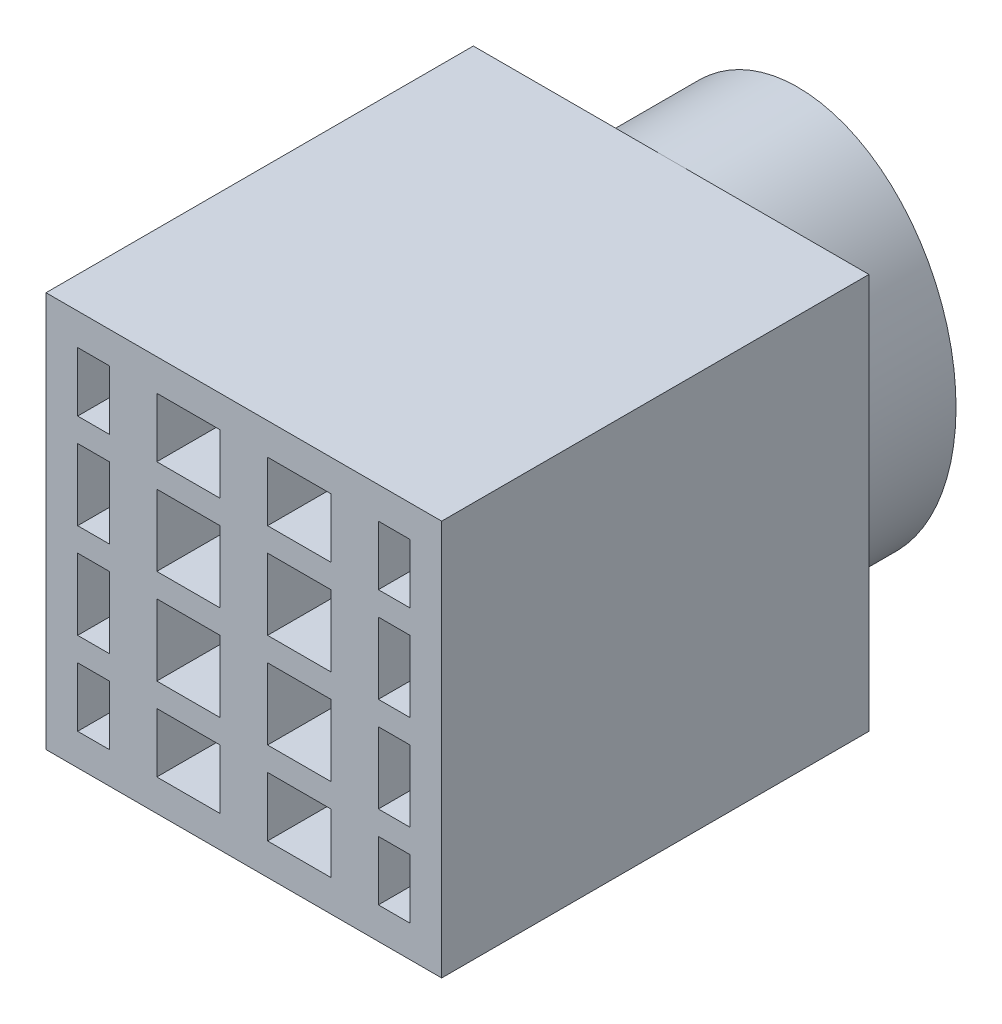
SolidWorks part; units mm, degrees
ref_plane "前视基准面" through (0, 0, 0) normal (0, 0, 1) x (1, 0, 0)
ref_plane "上视基准面" through (0, 0, 0) normal (0, 1, 0) x (1, 0, 0)
ref_plane "右视基准面" through (0, 0, 0) normal (1, 0, 0) x (0, 0, -1)
sketch "草图8" plane through (0, 0, 0) normal (0, 0, 1) x (1, 0, 0)
  line L0 (0, 7.8741) -> (0, -9.2542) construction
  line L1 (-12.5, -12.5) -> (12.5, -12.5)
  line L2 (-12.5, -12.5) -> (-12.5, 12.5)
  line L3 (-12.5, 12.5) -> (12.5, 12.5)
  line L4 (12.5, -12.5) -> (12.5, 12.5)
  line L5 (-12.5, -12.5) -> (12.5, 12.5) construction
  line L6 (-12.5, 12.5) -> (12.5, -12.5) construction
  line L7 (-16.0619, 0) -> (15.5648, 0) construction
  line L8 (-3.5, 7.8741) -> (-3.5, -9.2542) construction
  line L9 (-9.5, 7.8741) -> (-9.5, -9.2542) construction
  line L10 (5.5, 10.5) -> (1.5, 10.5)
  line L15 (-5.5, -10.5) -> (-1.5, -10.5)
  line L20 (-5.5, -10.5) -> (-5.5, 10.5)
  line L21 (-5.5, 10.5) -> (-1.5, 10.5)
  line L26 (-1.5, -10.5) -> (-1.5, 10.5)
  line L27 (-5.5, -10.5) -> (-1.5, 10.5) construction
  line L28 (-5.5, 10.5) -> (-1.5, -10.5) construction
  line L29 (-10.5, -10.5) -> (-8.5, -10.5)
  line L30 (-10.5, -10.5) -> (-10.5, 10.5)
  line L31 (-10.5, 10.5) -> (-8.5, 10.5)
  line L32 (-8.5, -10.5) -> (-8.5, 10.5)
  line L33 (-10.5, -10.5) -> (-8.5, 10.5) construction
  line L34 (-10.5, 10.5) -> (-8.5, -10.5) construction
  line L35 (1.5, -10.5) -> (1.5, 10.5)
  line L36 (5.5, -10.5) -> (1.5, -10.5)
  line L37 (5.5, -10.5) -> (5.5, 10.5)
  line L38 (10.5, 10.5) -> (8.5, 10.5)
  line L39 (8.5, -10.5) -> (8.5, 10.5)
  line L40 (10.5, -10.5) -> (8.5, -10.5)
  line L41 (10.5, -10.5) -> (10.5, 10.5)
  point P0 (0, 0)
  point P14 (-7, 0)
  point P15 (-3.5, 0)
  point P17 (-3, 0)
  point P21 (-9.5, 0)
  point P22 (-9, 0)
  dimension "D1" = 3.5
  dimension "D2" = 6
extrude "凸台-拉伸7" add sketch "草图8" along normal blind 25
sketch "草图9" plane through (0, 0, 0) normal (0, 0, -1) x (-1, 0, 0)
  line L1 (-12.5, -12.5) -> (12.5, -12.5)
  line L2 (-12.5, -12.5) -> (-12.5, 12.5)
  line L3 (-12.5, 12.5) -> (12.5, 12.5)
  line L4 (12.5, -12.5) -> (12.5, 12.5)
  line L5 (-12.5, -12.5) -> (12.5, 12.5) construction
  line L6 (-12.5, 12.5) -> (12.5, -12.5) construction
  point P0 (0, 0)
extrude "凸台-拉伸8" add sketch "草图9" along normal blind 2
sketch "草图14" plane through (0, 0, 25) normal (0, 0, 1) x (1, 0, 0)
  line L0 (-16.6961, 0) -> (20.7273, 0) construction
  line L1 (-12.5, 12.5) -> (-12.5, -12.5) construction
  line L2 (12.5, -0.75) -> (-12.5, -0.75)
  line L3 (12.5, -0.75) -> (12.5, 0.75)
  line L4 (12.5, 0.75) -> (-12.5, 0.75)
  line L5 (-12.5, -0.75) -> (-12.5, 0.75)
  line L6 (12.5, -0.75) -> (-12.5, 0.75) construction
  line L7 (12.5, 0.75) -> (-12.5, -0.75) construction
  line L12 (12.5, 5.25) -> (-12.5, 5.25)
  line L13 (12.5, 5.25) -> (12.5, 6.75)
  line L14 (12.5, 6.75) -> (-12.5, 6.75)
  line L15 (-12.5, 5.25) -> (-12.5, 6.75)
  line L16 (12.5, 5.25) -> (-12.5, 6.75) construction
  line L17 (12.5, 6.75) -> (-12.5, 5.25) construction
  line L18 (12.5, -6.75) -> (-12.5, -5.25) construction
  line L19 (12.5, -5.25) -> (-12.5, -6.75) construction
  line L20 (-12.5, -5.25) -> (-12.5, -6.75)
  line L21 (12.5, -6.75) -> (-12.5, -6.75)
  line L22 (12.5, -5.25) -> (12.5, -6.75)
  line L23 (12.5, -5.25) -> (-12.5, -5.25)
  point P3 (0, 0)
  point P11 (0, 6)
  point P19 (0, -6)
  dimension "D1" = 2
extrude "凸台-拉伸11" add sketch "草图14" against normal blind 25
sketch "草图16" plane through (0, 0, -2) normal (0, 0, -1) x (-1, 0, 0)
  line L1 (-20.8953, 0) -> (21.3992, 0) construction
  line L2 (0, 14.5627) -> (0, -19.3588) construction
  ellipse E0 centre (0, 0) end of major axis (0, -12.5) minor radius 10
  ellipse E1 centre (0, 0) end of major axis (0, -10.5) minor radius 8
extrude "凸台-拉伸14" add sketch "草图16" along normal blind 6
sketch "草图22" plane through (0, 0, -8) normal (0, 0, -1) x (-1, 0, 0)
  ellipse E0 centre (0, 0) end of major axis (0, -12.5) minor radius 10 construction
  ellipse E1 centre (0, 0) end of major axis (0, -12.5) minor radius 10
extrude "凸台-拉伸18" add sketch "草图22" along normal blind 2
sketch "草图23" plane through (0, 12.5, 0) normal (0, 1, 0) x (1, 0, 0)
  line L0 (-6.9262, -25) -> (-6.9262, 2)
  line L3 (12.5, -25) -> (-12.5, -25) construction
  line L4 (-12.5, 2) -> (0, 2) construction
  line L5 (-12.5, -20) -> (12.5, -20)
  line L6 (-12.5, -25) -> (-12.5, 2) construction
  line L7 (12.5, -25) -> (12.5, 2) construction
  dimension "D1" = 5
sketch "草图24" plane through (0, -12.5, 0) normal (0, -1, 0) x (1, 0, 0)
  line L0 (-12.5, 20) -> (12.5, 20)
  line L1 (-6.9262, 25) -> (-6.9262, -2)
